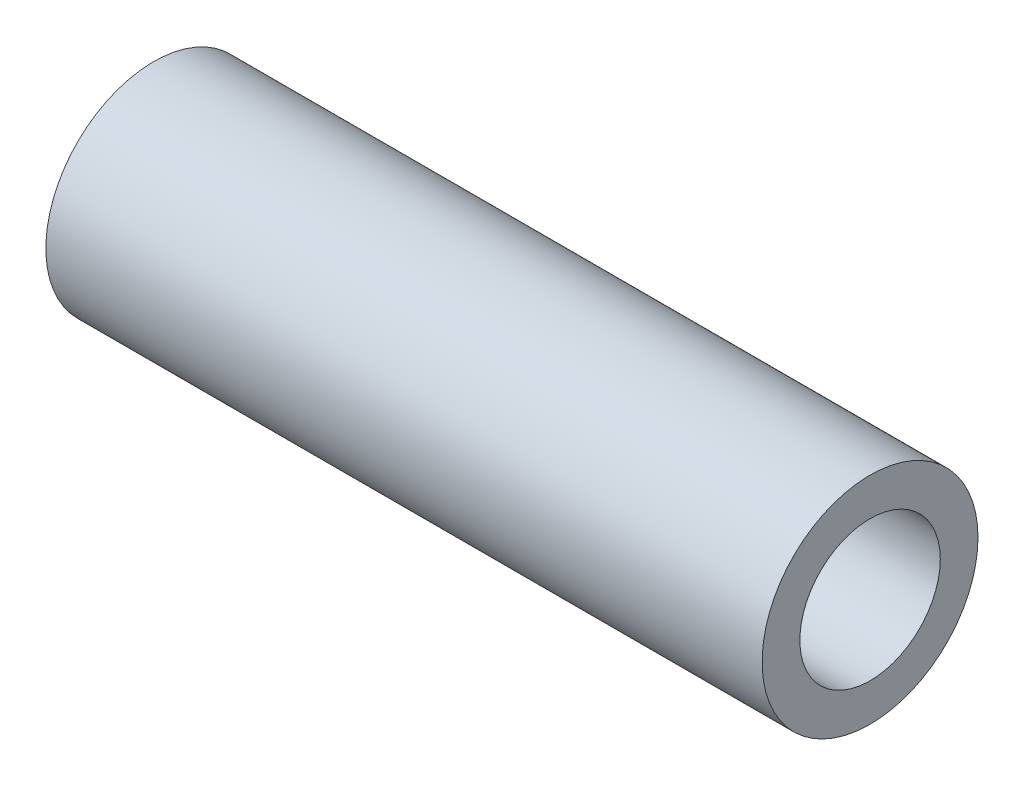
SolidWorks part; units mm, degrees
ref_plane "Front Plane" through (0, 0, 0) normal (0, 0, 1) x (1, 0, 0)
ref_plane "Top Plane" through (0, 0, 0) normal (0, 1, 0) x (1, 0, 0)
ref_plane "Right Plane" through (0, 0, 0) normal (1, 0, 0) x (0, 0, -1)
sketch "Sketch1" plane through (0, 0, 0) normal (1, 0, 0) x (0, 0, -1)
  circle A0 centre (0, 0) radius 1.27
  circle A1 centre (0, 0) radius 1.9522
  dimension "D1" = 2.54
extrude "Extrude1" add sketch "Sketch1" along normal mid plane 12.954
